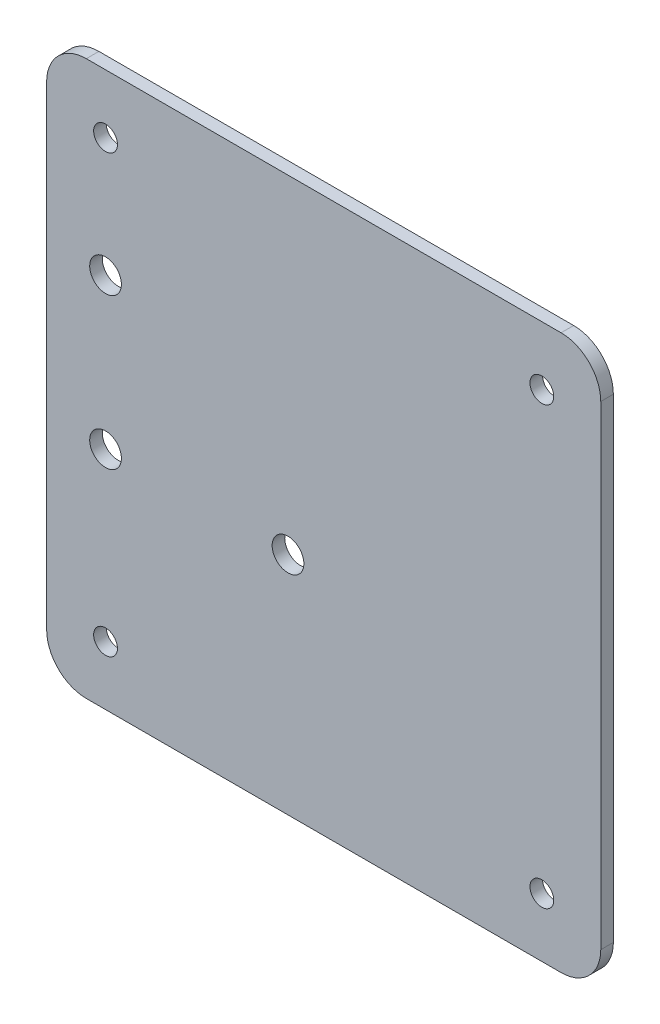
SolidWorks part; units mm, degrees
ref_plane "Front Plane" through (0, 0, 0) normal (0, 0, 1) x (1, 0, 0)
ref_plane "Top Plane" through (0, 0, 0) normal (0, 1, 0) x (1, 0, 0)
ref_plane "Right Plane" through (0, 0, 0) normal (1, 0, 0) x (0, 0, -1)
sketch "Sketch1" plane through (0, 0, 0) normal (0, 0, 1) x (1, 0, 0)
  line L1 (66.6353, 1721.56) -> (186.3353, 1721.56)
  line L2 (56.6353, 1711.56) -> (56.6353, 1591.86)
  line L3 (66.6353, 1581.86) -> (186.3353, 1581.86)
  line L4 (196.3353, 1711.56) -> (196.3353, 1591.86)
  line L5 (-97.883, 1661.0458) -> (174.117, 1661.0458) construction
  arc A0 (56.6353, 1591.86) -> (66.6353, 1581.86) centre (66.6353, 1591.86) ccw
  arc A1 (186.3353, 1581.86) -> (196.3353, 1591.86) centre (186.3353, 1591.86) ccw
  arc A2 (186.3353, 1721.56) -> (196.3353, 1711.56) centre (186.3353, 1711.56) cw
  arc A3 (66.6353, 1721.56) -> (56.6353, 1711.56) centre (66.6353, 1711.56) ccw
  point P10 (56.6353, 1581.86)
  point P13 (196.3353, 1581.86)
  dimension "D2" = 10
  dimension "D1" = 139.7
  dimension "D4" = 35
extrude "Boss-Extrude1" add sketch "Sketch1" along normal blind 3.175
sketch "Sketch2" plane through (0, 0, 0) normal (0, 0, -1) x (-1, 0, 0)
  line L0 (-71.4853, 1626.1374) -> (-71.4853, 1679.6302) construction
  line L1 (-117.4853, 1626.1374) -> (-117.4853, 1673.5664) construction
  line L2 (-71.4853, 1638.71) -> (-117.4853, 1638.71) construction
  line L3 (97.883, 1661.0458) -> (-207.117, 1661.0458) construction
  line L13 (-196.3353, 1651.71) -> (-56.6353, 1651.71) construction
  line L14 (-196.3353, 1591.86) -> (-196.3353, 1711.56) construction
  line L15 (-56.6353, 1711.56) -> (-56.6353, 1591.86) construction
  line L16 (-186.3353, 1721.56) -> (-66.6353, 1721.56) construction
  line L21 (-71.4853, 1596.71) -> (-71.4853, 1706.71) construction
  line L22 (-181.4853, 1596.71) -> (-71.4853, 1596.71) construction
  line L23 (-181.4853, 1706.71) -> (-181.4853, 1596.71) construction
  line L24 (-71.4853, 1706.71) -> (-181.4853, 1706.71) construction
  line L25 (-126.4853, 1721.56) -> (-126.4853, 1581.86) construction
  line L26 (-66.6353, 1581.86) -> (-186.3353, 1581.86) construction
  circle A3 centre (-71.4853, 1638.71) radius 4
  circle A4 centre (-71.4853, 1676.71) radius 4
  circle A5 centre (-117.4853, 1638.71) radius 4
  circle A6 centre (-181.4853, 1706.71) radius 3
  circle A7 centre (-71.4853, 1706.71) radius 3
  circle A8 centre (-181.4853, 1596.71) radius 3
  circle A9 centre (-71.4853, 1596.71) radius 3
  dimension "D1" = 8
  dimension "D3" = 6
  dimension "D4" = 15.6642
  dimension "D5" = 22.3358
  dimension "D6" = 9
  dimension "D7" = 46
  dimension "D8" = 55
  dimension "D2" = 55
  dimension "D9" = 55
  dimension "D10" = 55
extrude "Cut-Extrude1" cut sketch "Sketch2" against normal through all
